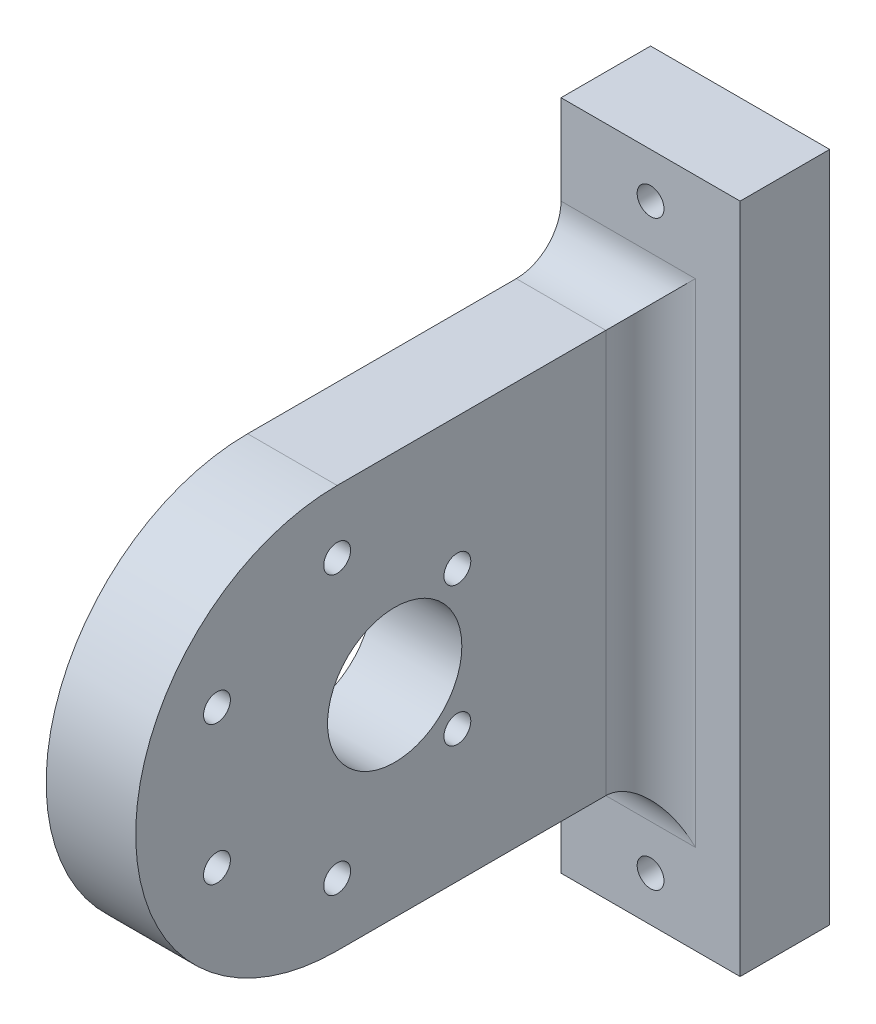
SolidWorks part; units mm, degrees
ref_plane "Front Plane" through (0, 0, 0) normal (0, 0, 1) x (1, 0, 0)
ref_plane "Top Plane" through (0, 0, 0) normal (0, 1, 0) x (1, 0, 0)
ref_plane "Right Plane" through (0, 0, 0) normal (1, 0, 0) x (0, 0, -1)
sketch "Sketch1" plane through (0, 0, 0) normal (1, 0, 0) x (0, 0, -1)
  line L0 (0, 0) -> (35, 0)
  line L1 (0, 0) -> (0, 22.5) construction
  line L2 (0, 45) -> (35, 45)
  line L3 (35, 45) -> (35, 60)
  line L4 (35, 0) -> (35, -15)
  line L5 (35, -15) -> (45, -15)
  line L6 (45, -15) -> (45, 60)
  line L7 (35, 60) -> (45, 60)
  line L8 (0, 22.5) -> (0, 38) construction
  arc A0 (0, 0) -> (0, 45) centre (0, 22.5) cw
  circle A1 centre (6.4234, 22.5) radius 7.5
  circle A2 centre (13.4234, 30.25) radius 1.5
  circle A3 centre (0, 38) radius 1.5
  circle A4 centre (-13.4234, 30.25) radius 1.5
  circle A5 centre (-13.4234, 14.75) radius 1.5
  circle A6 centre (0, 7) radius 1.5
  circle A7 centre (13.4234, 14.75) radius 1.5
  dimension "D7" = 3
  dimension "D8" = 3
  dimension "D9" = 3
  dimension "D10" = 3
  dimension "D11" = 3
  dimension "D12" = 3
  dimension "D14" = 15
  dimension "D1" = 35
  dimension "D2" = 22.5
  dimension "D3" = 15
  dimension "D4" = 15
  dimension "D5" = 10
  dimension "D6" = 15.5
extrude "Boss-Extrude1" add sketch "Sketch1" along normal blind 10
fillet "Fillet1" radius 5 1 edges at (5, 45, -35)
fillet "Fillet2" radius 5 1 edges at (5, 0, -35)
sketch "Sketch2" plane through (10, 0, 0) normal (1, 0, 0) x (0, 0, -1)
  line L1 (45, 60) -> (35, 60)
  line L2 (45, 60) -> (45, -15)
  line L3 (45, -15) -> (35, -15)
  line L4 (35, 60) -> (35, -15)
extrude "Boss-Extrude2" add sketch "Sketch2" along normal blind 10
fillet "Fillet3" radius 5 3 edges at (10, 46.4645, -33.5355) (10, -1.4645, -33.5355) (10, 22.5, -35)
sketch "Sketch3" plane through (0, 0, -35) normal (0, 0, 1) x (1, 0, 0)
  circle A0 centre (10, -10) radius 1.5
  circle A1 centre (10, 55) radius 1.5
  point P7 (33.8576, 57.3385)
  point P16 (11.139, 55.0421)
  dimension "D3" = 3
  dimension "D4" = 3
  dimension "D1" = 10
  dimension "D2" = 5
  dimension "D5" = 10
  dimension "D6" = 5
extrude "Cut-Extrude1" cut sketch "Sketch3" against normal blind 10
